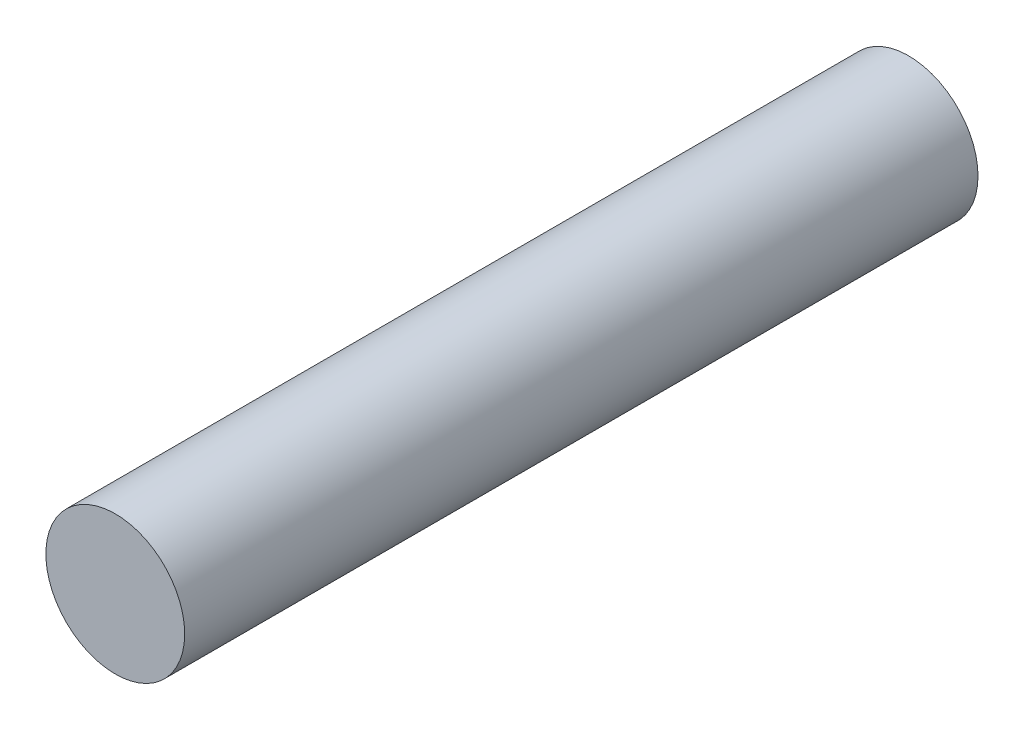
SolidWorks part; units mm, degrees
material "Stainless Steel (ferritic)"
ref_plane "Front Plane" through (0, 0, 0) normal (0, 0, 1) x (1, 0, 0)
ref_plane "Top Plane" through (0, 0, 0) normal (0, 1, 0) x (1, 0, 0)
ref_plane "Right Plane" through (0, 0, 0) normal (1, 0, 0) x (0, 0, -1)
sketch "Sketch1" plane through (0, 0, 0) normal (0, 0, 1) x (1, 0, 0)
  circle A0 centre (0, 0) radius 1.75
  dimension "D1" = 3.5
extrude "Boss-Extrude1" add sketch "Sketch1" along normal blind 20
